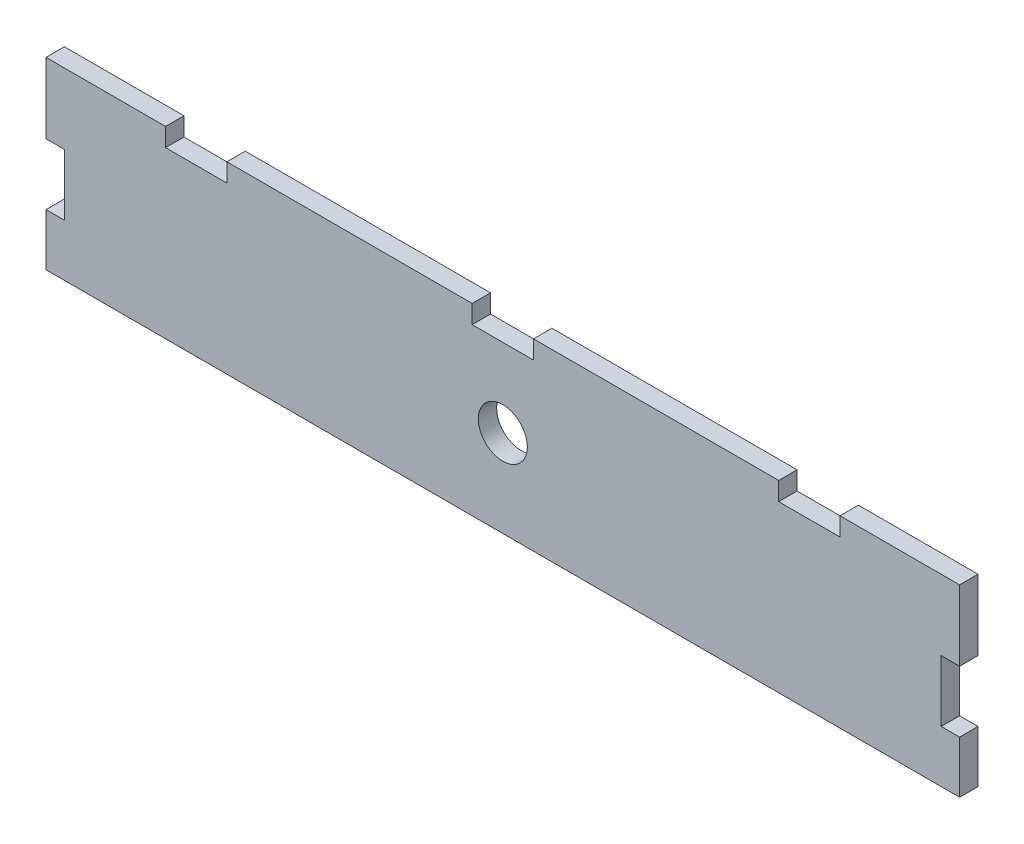
SolidWorks part; units mm, degrees
ref_plane "Front Plane" through (0, 0, 0) normal (0, 0, 1) x (1, 0, 0)
ref_plane "Top Plane" through (0, 0, 0) normal (0, 1, 0) x (1, 0, 0)
ref_plane "Right Plane" through (0, 0, 0) normal (1, 0, 0) x (0, 0, -1)
sketch "Sketch1" plane through (0, 0, 0) normal (0, 0, 1) x (1, 0, 0)
  line L2 (-74.5, 3) -> (-74.5, -8.5)
  line L3 (-74.5, -27) -> (74.5, -27)
  line L4 (74.5, 3) -> (74.5, -8.5)
  line L7 (-5, 3) -> (-5, 0)
  line L8 (-5, 0) -> (5, 0)
  line L9 (5, 3) -> (5, 0)
  line L11 (45, 3) -> (45, 0)
  line L12 (45, 0) -> (55, 0)
  line L13 (55, 3) -> (55, 0)
  line L27 (71.5, -8.5) -> (74.5, -8.5)
  line L28 (71.5, -8.5) -> (71.5, -18.5)
  line L29 (71.5, -18.5) -> (74.5, -18.5)
  line L31 (-71.5, -18.5) -> (-74.5, -18.5)
  line L32 (-71.5, -8.5) -> (-71.5, -18.5)
  line L33 (-71.5, -8.5) -> (-74.5, -8.5)
  line L34 (-74.5, -18.5) -> (-74.5, -27)
  line L35 (74.5, -18.5) -> (74.5, -27)
  line L36 (0, -55) -> (0, 55) construction
  line L37 (-55, 3) -> (-55, 0)
  line L38 (-45, 0) -> (-55, 0)
  line L39 (-45, 3) -> (-45, 0)
  line L41 (74.5, 3) -> (55, 3)
  line L42 (-55, 3) -> (-74.5, 3)
  line L43 (-5, 3) -> (-45, 3)
  line L44 (45, 3) -> (5, 3)
  point P0 (0, -27)
  point P12 (0, 0)
  dimension "D1" = 3
  dimension "D2" = 149
  dimension "D3" = 3
  dimension "D4" = 30
  dimension "D5" = 10
  dimension "D7" = 3
  dimension "D8" = 10
  dimension "D9" = 8.5
  dimension "D6" = 40
extrude "Boss-Extrude1" add sketch "Sketch1" along normal blind 3
sketch "Sketch2" plane through (0, 0, 0) normal (0, 0, 1) x (1, 0, 0)
  line L0 (-74.5, -27) -> (74.5, -27) construction
  line L1 (0, -1.65) -> (0, 1.65) construction
  circle A0 centre (0, -12.79) radius 4
  point P6 (0, 0)
  dimension "D1" = 14.21
  dimension "D2" = 8
extrude "Cut-Extrude1" cut sketch "Sketch2" along normal through all
